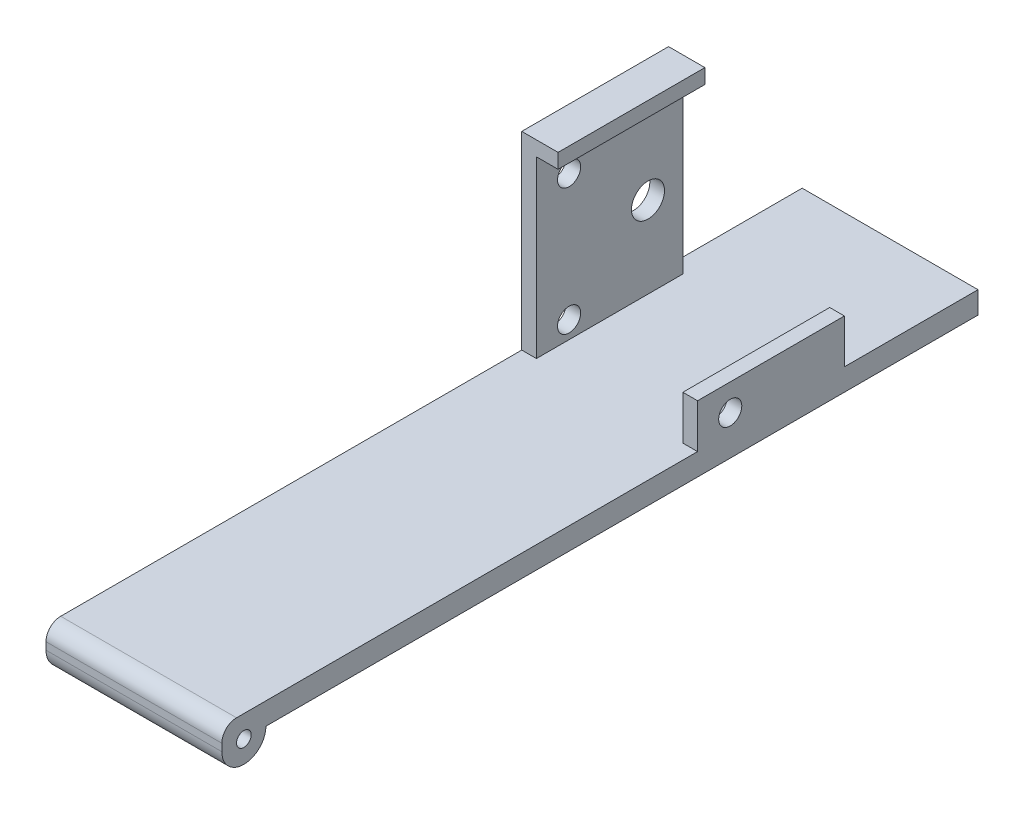
SolidWorks part; units mm, degrees
ref_plane "Front Plane" through (0, 0, 0) normal (0, 0, 1) x (1, 0, 0)
ref_plane "Top Plane" through (0, 0, 0) normal (0, 1, 0) x (1, 0, 0)
ref_plane "Right Plane" through (0, 0, 0) normal (1, 0, 0) x (0, 0, -1)
sketch "Sketch1" plane through (0, 0, 0) normal (1, 0, 0) x (0, 0, -1)
  line L1 (21.7682, 1.933) -> (-79.2318, 1.933)
  line L2 (21.7682, 1.933) -> (21.7682, -1.067)
  line L3 (21.7682, -1.067) -> (-75.2318, -1.067)
  line L4 (-81.2318, -0.067) -> (-81.2318, -1.067)
  arc A0 (-81.2318, -1.067) -> (-75.2318, -1.067) centre (-78.2318, -1.067) ccw
  arc A1 (-79.2318, 1.933) -> (-81.2318, -0.067) centre (-79.2318, -0.067) ccw
  circle A2 centre (-78.2318, -1.067) radius 1
  point P9 (0, 0)
  dimension "D3" = 6
  dimension "D4" = 2
  dimension "D5" = 2
  dimension "D1" = 3
  dimension "D2" = 103
extrude "Boss-Extrude1" add sketch "Sketch1" along normal mid plane 23.95
sketch "Sketch2" plane through (11.975, 0, 0) normal (1, 0, 0) x (0, 0, -1)
  line L0 (-16.4315, 25.733) -> (-16.4315, 1.933)
  line L1 (-16.4315, 1.933) -> (3.5685, 1.933)
  line L3 (3.5685, 25.733) -> (-16.4315, 25.733)
  line L4 (21.7682, -1.067) -> (21.7682, 1.933) construction
  line L5 (3.5685, 25.733) -> (3.5685, 1.933)
  line L6 (21.7682, 1.933) -> (-79.2318, 1.933) construction
  circle A0 centre (-11.9815, 4.308) radius 1.575
  circle A1 centre (-11.9815, 21.558) radius 1.575
  circle A4 centre (-1.2315, 13.033) radius 2.25
  dimension "D3" = 3.15
  dimension "D4" = 3.15
  dimension "D5" = 4.5
  dimension "D7" = 4.175
  dimension "D8" = 2.375
  dimension "D9" = 11.1
  dimension "D1" = 23.8
  dimension "D2" = 20
  dimension "D6" = 0
  dimension "D10" = 18.1998
  dimension "D11" = 4.45
  dimension "D12" = 4.45
  dimension "D13" = 4.8
extrude "Boss-Extrude2" add sketch "Sketch2" against normal blind 2
mirror "Mirror1" about plane through (0, 0, 0) normal (1, 0, 0) of "Boss-Extrude2"
sketch "Sketch3" plane through (0, 25.733, 0) normal (0, 1, 0) x (1, 0, 0)
  line L1 (-11.975, 3.5685) -> (11.975, 3.5685)
  line L2 (-11.975, 3.5685) -> (-11.975, -16.4315)
  line L3 (-11.975, -16.4315) -> (11.975, -16.4315)
  line L4 (11.975, 3.5685) -> (11.975, -16.4315)
extrude "Boss-Extrude3" add sketch "Sketch3" along normal blind 2
sketch "Sketch4" plane through (11.975, 0, 0) normal (1, 0, 0) x (0, 0, -1)
  line L0 (-16.4315, 27.733) -> (-16.4315, 1.933) construction
  line L1 (-16.4315, 1.933) -> (-79.2318, 1.933) construction
  line L2 (-16.4315, 7.933) -> (3.5685, 7.933)
  line L3 (-16.4315, 7.933) -> (-16.4315, 27.733)
  line L4 (-16.4315, 27.733) -> (3.5685, 27.733)
  line L5 (3.5685, 7.933) -> (3.5685, 27.733)
  dimension "D1" = 6
extrude "Cut-Extrude1" cut sketch "Sketch4" against normal blind 19
